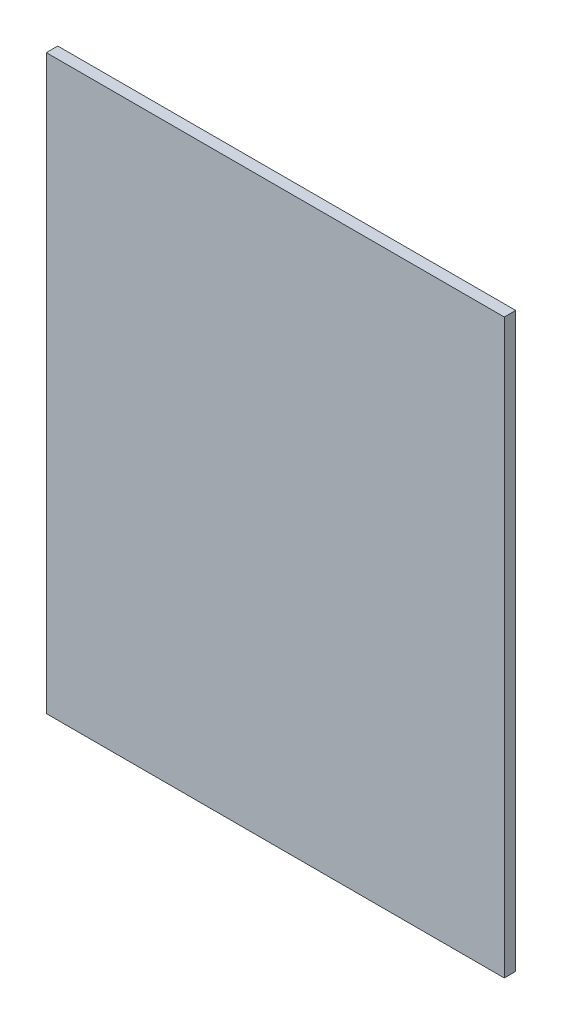
SolidWorks part; units mm, degrees
ref_plane "前视基准面" through (0, 0, 0) normal (0, 0, 1) x (1, 0, 0)
ref_plane "上视基准面" through (0, 0, 0) normal (0, 1, 0) x (1, 0, 0)
ref_plane "右视基准面" through (0, 0, 0) normal (1, 0, 0) x (0, 0, -1)
sketch "草图1" plane through (0, 0, 0) normal (0, 0, 1) x (1, 0, 0)
  line L1 (-200, 250) -> (200, 250)
  line L2 (-200, 250) -> (-200, -250)
  line L3 (-200, -250) -> (200, -250)
  line L4 (200, 250) -> (200, -250)
  line L5 (-200, 250) -> (200, -250) construction
  line L6 (-200, -250) -> (200, 250) construction
  point P0 (0, 0)
  dimension "D1" = 400
  dimension "D2" = 500
extrude "凸台-拉伸1" add sketch "草图1" along normal blind 10
